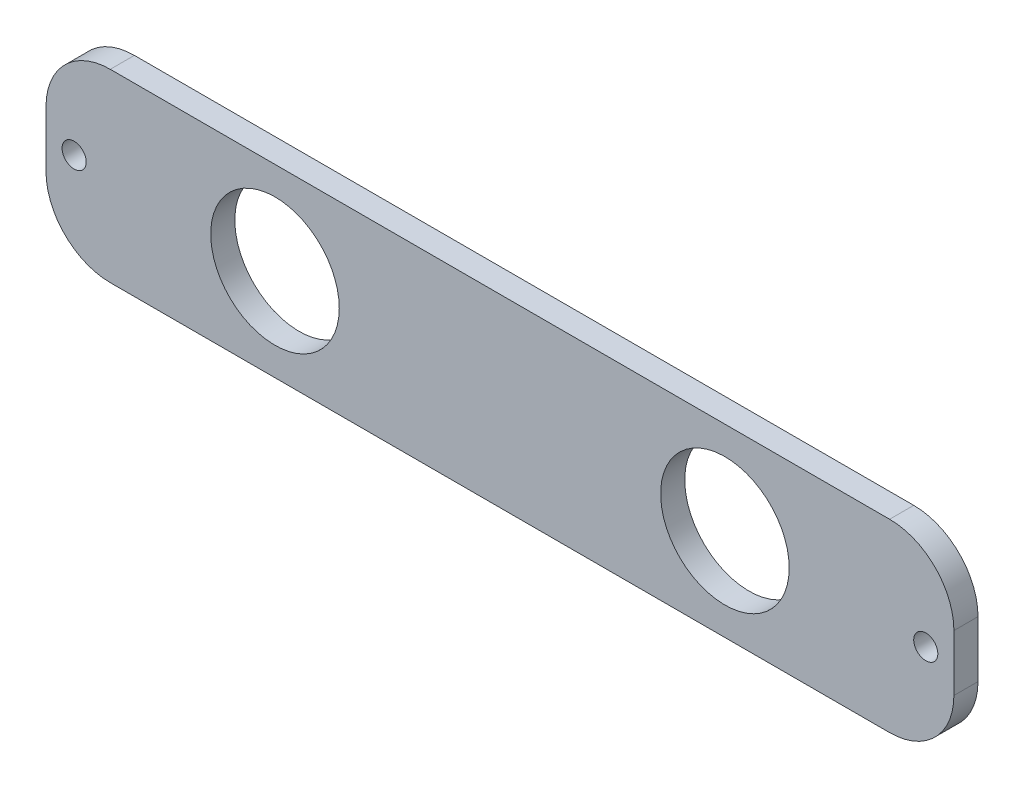
SolidWorks part; units mm, degrees
material "PBT 一般用途"
ref_plane "前视基准面" through (0, 0, 0) normal (0, 0, 1) x (1, 0, 0)
ref_plane "上视基准面" through (0, 0, 0) normal (0, 1, 0) x (1, 0, 0)
ref_plane "右视基准面" through (0, 0, 0) normal (1, 0, 0) x (0, 0, -1)
other "Configuration Table"
sketch "草图1" plane through (0, 0, 0) normal (0, 0, 1) x (1, 0, 0)
  line L0 (-41.4188, 30.5585) -> (55.5812, 30.5585)
  line L1 (-49.4188, 22.5585) -> (-49.4188, 15.5585)
  line L2 (-41.4188, 7.5585) -> (55.5812, 7.5585)
  line L3 (63.5812, 15.5585) -> (63.5812, 22.5585)
  arc A0 (-49.4188, 22.5585) -> (-41.4188, 30.5585) centre (-41.4188, 22.5585) cw
  arc A1 (55.5812, 7.5585) -> (63.5812, 15.5585) centre (55.5812, 15.5585) ccw
  arc A2 (63.5812, 22.5585) -> (55.5812, 30.5585) centre (55.5812, 22.5585) ccw
  arc A3 (-41.4188, 7.5585) -> (-49.4188, 15.5585) centre (-41.4188, 15.5585) cw
  circle A4 centre (-45.9188, 19.0585) radius 1.5
  circle A5 centre (60.0812, 19.0585) radius 1.5
  circle A6 centre (-20.9188, 19.0585) radius 8
  circle A7 centre (35.0812, 19.0585) radius 8
  point P14 (-45.9188, 19.0585)
  point P15 (60.0812, 19.0585)
  point P20 (-20.9188, 19.0585)
  point P21 (35.0812, 19.0585)
  dimension "D1" = 8
  dimension "D2" = 8
  dimension "D6" = 106
  dimension "D7" = 25
  dimension "D3" = 3.5
  dimension "D4" = 11.5
  dimension "D5" = 23
  dimension "D8" = 25
extrude "凸台-拉伸2" add sketch "草图1" along normal blind 3 contours L0 A2 L3 A1 L2 A3 L1 A0
sketch "草图5" plane through (0, 0, 3) normal (0, 0, 1) x (1, 0, 0)
  line L0 (-49.4188, 22.5585) -> (-49.4188, 15.5585) construction
  line L3 (-41.4188, 7.5585) -> (55.5812, 7.5585) construction
  circle A0 centre (-45.9188, 19.0585) radius 1.5
  circle A1 centre (60.0812, 19.0585) radius 1.5
  circle A2 centre (-20.9188, 19.0585) radius 8
  circle A3 centre (35.0812, 19.0585) radius 8
  point P0 (-45.9188, 19.0585)
  point P5 (60.0812, 19.0585)
  point P10 (-20.9188, 19.0585)
  point P11 (35.0812, 19.0585)
  point P12 (60.0812, 19.0585)
  dimension "D3" = 106
  dimension "D4" = 25
  dimension "D1" = 3.5
  dimension "D2" = 11.5
  dimension "D5" = 25
extrude "切除-拉伸1" cut sketch "草图5" against normal blind 3
